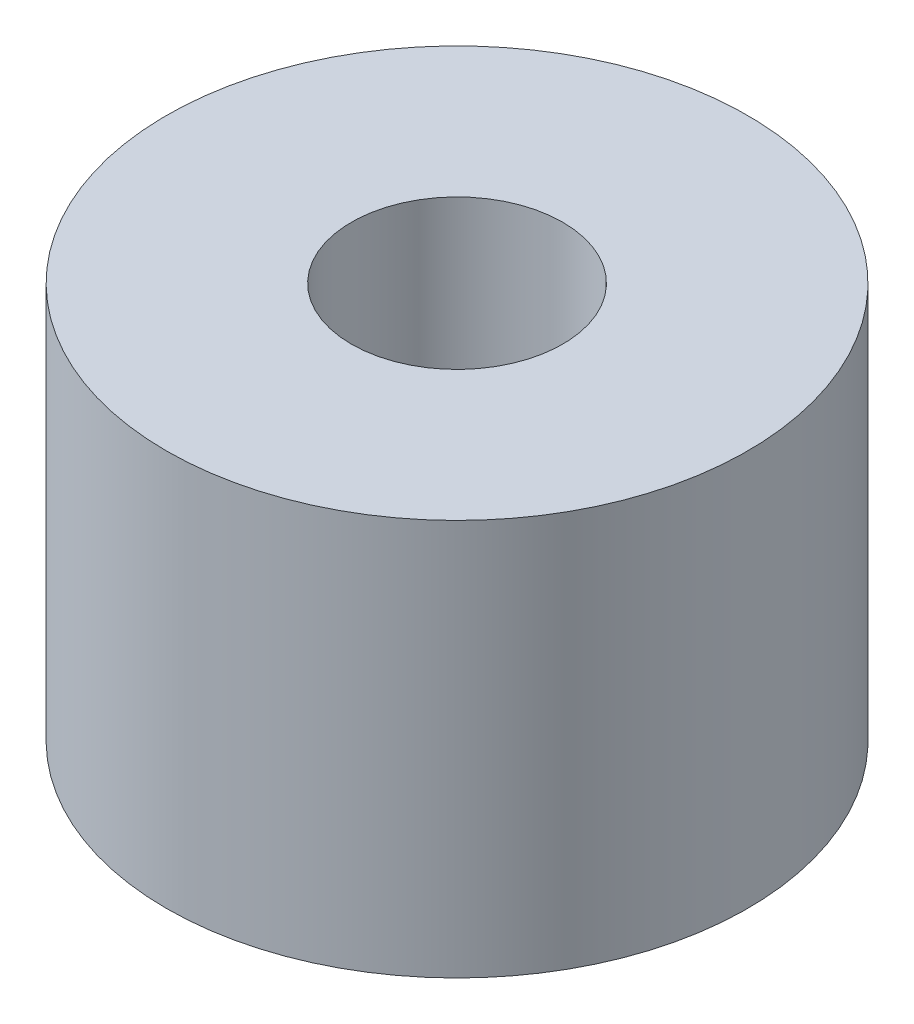
SolidWorks part; units mm, degrees
ref_plane "Płaszczyzna przednia" through (0, 0, 0) normal (0, 0, 1) x (1, 0, 0)
ref_plane "Płaszczyzna górna" through (0, 0, 0) normal (0, 1, 0) x (1, 0, 0)
ref_plane "Płaszczyzna prawa" through (0, 0, 0) normal (1, 0, 0) x (0, 0, -1)
sketch "Szkic1" plane through (0, 0, 0) normal (0, 1, 0) x (1, 0, 0)
  circle A0 centre (0, 0) radius 11
  dimension "D1" = 22
extrude "Dodanie-wyciągnięcie1" add sketch "Szkic1" along normal blind 15
hole_wizard "Otwory ustalające Ø8.0mm1" positions "Szkic2" profile "Szkic3" hole size "Ø8.0" standard "Ansi Metric" end condition through all
sketch "Szkic2" plane through (0, 15, 0) normal (0, 1, 0) x (1, 0, 0)
  point P0 (0, 0)
sketch "Szkic3" plane through (0, 15, 0) normal (1, 0, 0) x (0, 0, 1)
  line L0 (0, 0) -> (0, 15)
  line L1 (0, 15) -> (4, 15)
  line L2 (4, 15) -> (4, 0)
  line L5 (4, 0) -> (0, 0)
  line L11 (0, -6.35) -> (0, 107.95) construction
  dimension "Średnica otworu na wylot" = 8
  dimension "Głębokość otworu na wylot" = 15
sketch "Szkic4" plane through (0, 0, 0) normal (0, -1, 0) x (1, 0, 0)
  line L0 (0, 0) -> (27.5, 0) construction
  circle A0 centre (27.5, 0) radius 3.9155
  dimension "D1" = 27.5
